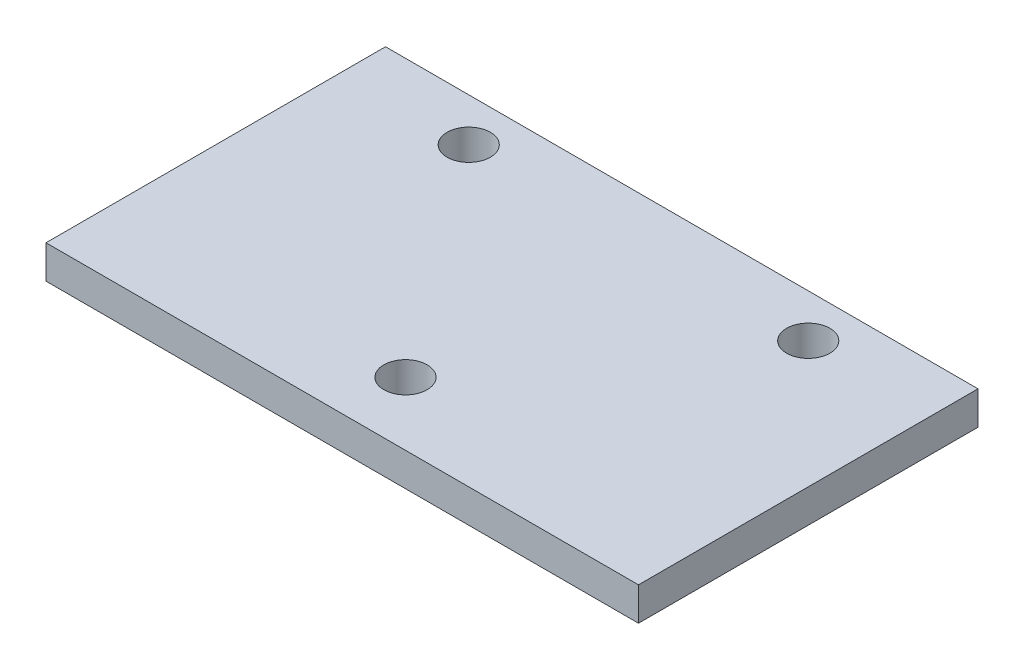
SolidWorks part; units mm, degrees
material "PW30:2:Sc:0:"
ref_plane "Front" through (0, 0, 0) normal (0, 0, 1) x (1, 0, 0)
ref_plane "Top" through (0, 0, 0) normal (0, 1, 0) x (1, 0, 0)
ref_plane "Right" through (0, 0, 0) normal (1, 0, 0) x (0, 0, -1)
sketch "Sketch1" plane through (0, 0, 0) normal (0, 1, 0) x (1, 0, 0)
  line L0 (-89, -51) -> (89, -51)
  line L1 (-89, -51) -> (-89, 51)
  line L2 (89, 51) -> (-89, 51)
  line L3 (89, 51) -> (89, -51)
  line L4 (-89, 51) -> (89, -51) construction
  dimension "D1" = 102
  dimension "D2" = 178
extrude "Plate" add sketch "Sketch1" along normal blind 10
sketch "Sketch2" plane through (0, 10, 0) normal (0, 1, 0) x (-1, 0, 0)
  line L1 (89, 51) -> (89, -51) construction
  line L2 (-89, -51) -> (89, -51) construction
  line L4 (0, -51) -> (0, 78.8221) construction
  circle A0 centre (51, -38) radius 6.5
  circle A1 centre (-51, -38) radius 6.5
  circle A2 centre (0, 32) radius 6.5
  dimension "D2" = 13
  dimension "D3" = 38
  dimension "D1" = 13
  dimension "D4" = 70
extrude "Holes" cut sketch "Sketch2" against normal through all
